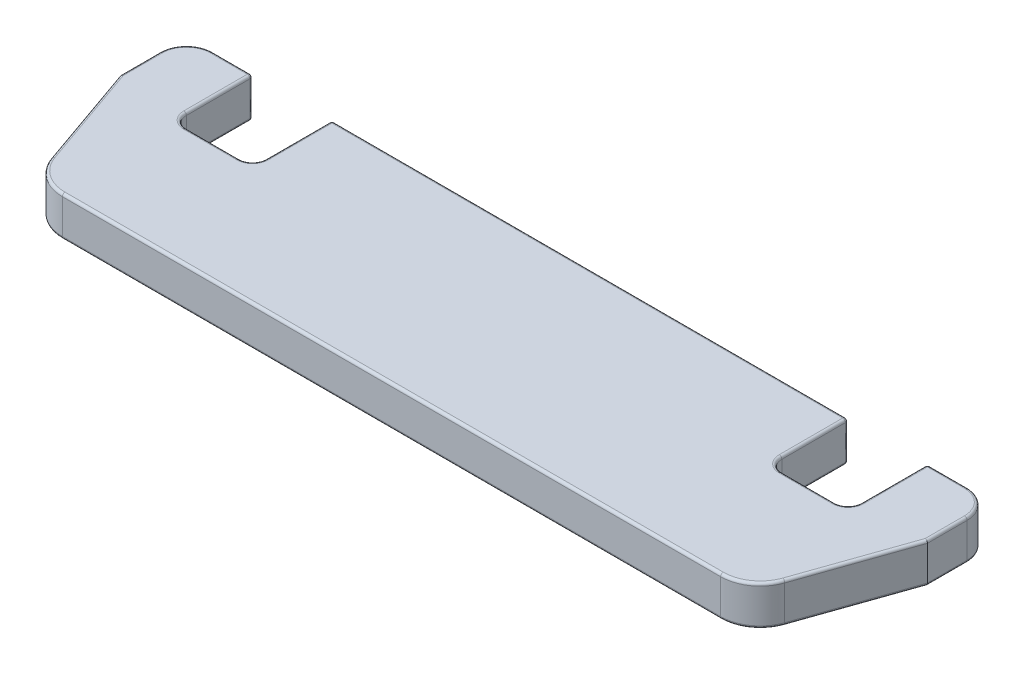
SolidWorks part; units mm, degrees
ref_plane "Front Plane" through (0, 0, 0) normal (0, 0, 1) x (1, 0, 0)
ref_plane "Top Plane" through (0, 0, 0) normal (0, 1, 0) x (1, 0, 0)
ref_plane "Right Plane" through (0, 0, 0) normal (1, 0, 0) x (0, 0, -1)
sketch "Sketch1" plane through (0, 0, 0) normal (0, 1, 0) x (1, 0, 0)
  line L0 (0, 0) -> (0, 15) construction
  line L1 (19.5, 15) -> (-19.5, 15)
  line L2 (-19.5, 15) -> (-19.5, 10)
  line L3 (-20.5, 9) -> (-24.5, 9)
  line L4 (-25.5, 10) -> (-25.5, 15)
  line L5 (-25.5, 15) -> (-28.5, 15)
  line L6 (-30.5, 13) -> (-30.5, 10)
  line L7 (-30.5, 10) -> (-27.7031, 2.0089)
  line L8 (-24.8716, 0) -> (24.8716, 0)
  line L9 (30.5, 10) -> (27.7031, 2.0089)
  line L10 (30.5, 13) -> (30.5, 10)
  line L11 (25.5, 15) -> (28.5, 15)
  line L12 (25.5, 10) -> (25.5, 15)
  line L13 (20.5, 9) -> (24.5, 9)
  line L14 (19.5, 15) -> (19.5, 10)
  arc A0 (-19.5, 10) -> (-20.5, 9) centre (-20.5, 10) cw
  arc A1 (-24.5, 9) -> (-25.5, 10) centre (-24.5, 10) cw
  arc A2 (27.7031, 2.0089) -> (24.8716, 0) centre (24.8716, 3) cw
  arc A3 (-28.5, 15) -> (-30.5, 13) centre (-28.5, 13) ccw
  arc A4 (28.5, 15) -> (30.5, 13) centre (28.5, 13) cw
  arc A5 (-27.7031, 2.0089) -> (-24.8716, 0) centre (-24.8716, 3) ccw
  arc A6 (24.5, 9) -> (25.5, 10) centre (24.5, 10) ccw
  arc A7 (19.5, 10) -> (20.5, 9) centre (20.5, 10) ccw
  point P12 (-19.5, 9)
  point P15 (-25.5, 9)
  point P18 (-27, 0)
  point P21 (-30.5, 15)
  point P37 (30.5, 15)
  point P38 (27, 0)
  point P39 (25.5, 9)
  point P40 (19.5, 9)
  dimension "D8" = 1
  dimension "D9" = 2
  dimension "D10" = 3
  dimension "D1" = 15
  dimension "D2" = 6
  dimension "D3" = 5
  dimension "D4" = 5
  dimension "D5" = 19.5
  dimension "D6" = 27
  dimension "D7" = 6
extrude "Boss-Extrude1" add sketch "Sketch1" along normal blind 3
fillet "Fillet1" radius 0.2 48 edges at (-22.5, 0, -9) (-25.2071, 0, -9.2929) (-25.5, 0, -12.5) (-27, 0, -15) (-29.9142, 0, -14.4142) (-30.5, 0, -11.5) (-29.1016, 0, -6.0045) (0, 0, 0) (29.1016, 0, -6.0045) (30.5, 0, -11.5) (29.9142, 0, -14.4142) (27, 0, -15) (25.5, 0, -12.5) (25.2071, 0, -9.2929) (22.5, 0, -9) (19.7929, 0, -9.2929) (19.5, 0, -12.5) (0, 0, -15) (-19.5, 0, -12.5) (-19.7929, 0, -9.2929) (-19.5, 3, -12.5) (0, 3, -15) (19.5, 3, -12.5) (19.7929, 3, -9.2929) (22.5, 3, -9) (25.2071, 3, -9.2929) (25.5, 3, -12.5) (27, 3, -15) (29.9142, 3, -14.4142) (30.5, 3, -11.5) (29.1016, 3, -6.0045) (0, 3, 0) (-29.1016, 3, -6.0045) (-30.5, 3, -11.5) (-29.9142, 3, -14.4142) (-27, 3, -15) (-25.5, 3, -12.5) (-25.2071, 3, -9.2929) (-22.5, 3, -9) (-19.7929, 3, -9.2929) (-19.5, 1.5, -15) (25.5, 1.5, -15) (19.5, 1.5, -15) (-25.5, 1.5, -15) (-26.6075, 0, -0.5533) (26.6075, 0, -0.5533) (26.6075, 3, -0.5533) (-26.6075, 3, -0.5533)
